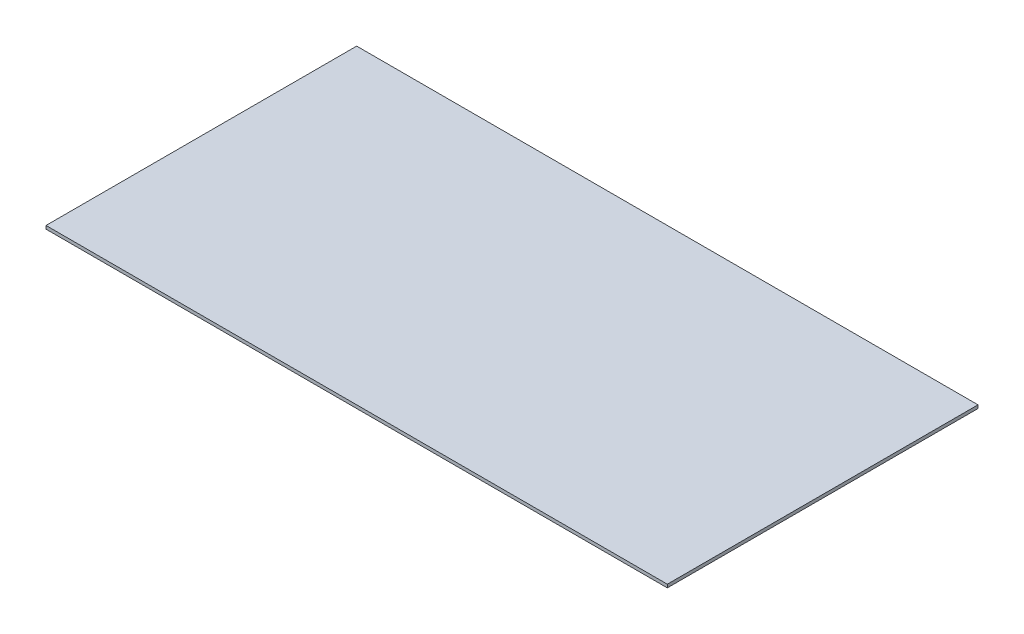
SolidWorks part; units mm, degrees
ref_plane "Front Plane" through (0, 0, 0) normal (0, 0, 1) x (1, 0, 0)
ref_plane "Top Plane" through (0, 0, 0) normal (0, 1, 0) x (1, 0, 0)
ref_plane "Right Plane" through (0, 0, 0) normal (1, 0, 0) x (0, 0, -1)
sketch "Sketch1" plane through (0, 0, 0) normal (0, 0, 1) x (1, 0, 0)
  line L0 (609.6, 0) -> (609.6, 3.175) construction
  line L1 (0, 0) -> (609.6, 0) construction
  point P6 (0, 0)
  dimension "Length" = 609.6
  dimension "Thickness" = 3.175
sketch "Sketch2" plane through (0, 0, 0) normal (1, 0, 0) x (0, 0, -1)
  line L0 (304.8, 0) -> (0, 0)
  point P4 (0, 0)
  dimension "Width" = 304.8
sketch "Sketch3" plane through (0, 0, 0) normal (0, 0, 1) x (1, 0, 0)
  line L5 (0, 0) -> (609.6, 0)
  line L6 (0, 0) -> (0, 3.175)
  line L7 (0, 3.175) -> (609.6, 3.175)
  line L8 (609.6, 0) -> (609.6, 3.175)
extrude "Boss-Extrude1" add sketch "Sketch3" against normal up to vertex (304.8 mm away) up to point (0, 0, -304.8)
